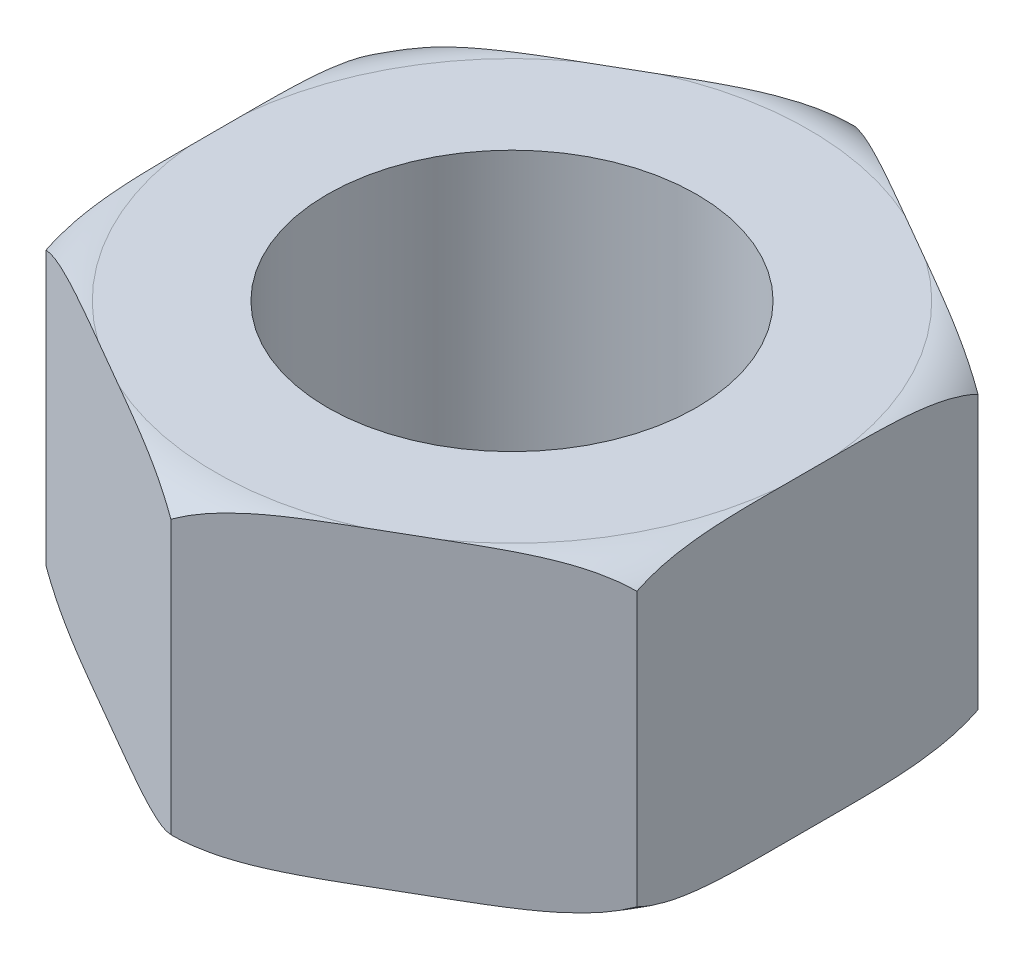
SolidWorks part; units mm, degrees
ref_plane "Ebene vorne" through (0, 0, 0) normal (0, 0, 1) x (1, 0, 0)
ref_plane "Ebene oben" through (0, 0, 0) normal (0, 1, 0) x (1, 0, 0)
ref_plane "Ebene rechts" through (0, 0, 0) normal (1, 0, 0) x (0, 0, -1)
sketch "Skizze1" plane through (0, 0, 0) normal (0, 1, 0) x (1, 0, 0)
  line L0 (0, 0) -> (0, -50000) construction
  line L1 (0, 9.2376) -> (-8, 4.6188)
  line L2 (-8, 4.6188) -> (-8, -4.6188)
  line L3 (-8, -4.6188) -> (0, -9.2376)
  line L4 (0, -9.2376) -> (8, -4.6188)
  line L5 (8, -4.6188) -> (8, 4.6188)
  line L6 (8, 4.6188) -> (0, 9.2376)
  circle A0 centre (0, 0) radius 8 construction
  circle A1 centre (0, 0) radius 5
  dimension "D2" = 10
  dimension "D1" = 16
extrude "Aufsatz-Linear austragen1" add sketch "Skizze1" along normal blind 8.4
sketch "Skizze2" plane through (0, 0, 0) normal (1, 0, 0) x (0, 0, -1)
  line L0 (0, 0) -> (0, -50000) construction
  line L1 (-4.6188, 0) -> (4.6188, 0) construction
  line L2 (-4.6188, 8.4) -> (4.6188, 8.4) construction
  line L3 (-4.6188, 0) -> (4.6188, 0) construction
  line L4 (-4.6188, 8.4) -> (4.6188, 8.4) construction
  line L5 (9.2376, 7.9) -> (-49990.7624, 7.9) construction
  line L7 (9.2376, 4.2) -> (-49990.7624, 4.2) construction
  line L8 (9.2376, 8.4) -> (9.2376, 0) construction
  line L9 (8.0376, 8.8155) -> (8.0376, -49991.1845) construction
  line L10 (4.6188, 8.4) -> (9.2376, 8.4) construction
  line L11 (8.0376, 8.4) -> (9.2376, 8.4)
  line L12 (9.2376, 8.4) -> (9.2376, 7.9)
  line L13 (8.0376, 0) -> (9.2376, 0)
  line L14 (9.2376, 0) -> (9.2376, 0.5)
  arc A0 (8.0376, 8.4) -> (9.2376, 7.9) centre (8.0376, 6.71) cw
  arc A1 (8.0376, 0) -> (9.2376, 0.5) centre (8.0376, 1.69) ccw
  point P13 (9.2376, 4.2)
  point P21 (9.2376, 7.9)
  dimension "D1" = 1.2
  dimension "D2" = 0.5
revolve "Schnitt-Rotation1" cut sketch "Skizze2" angle 360 about L0
